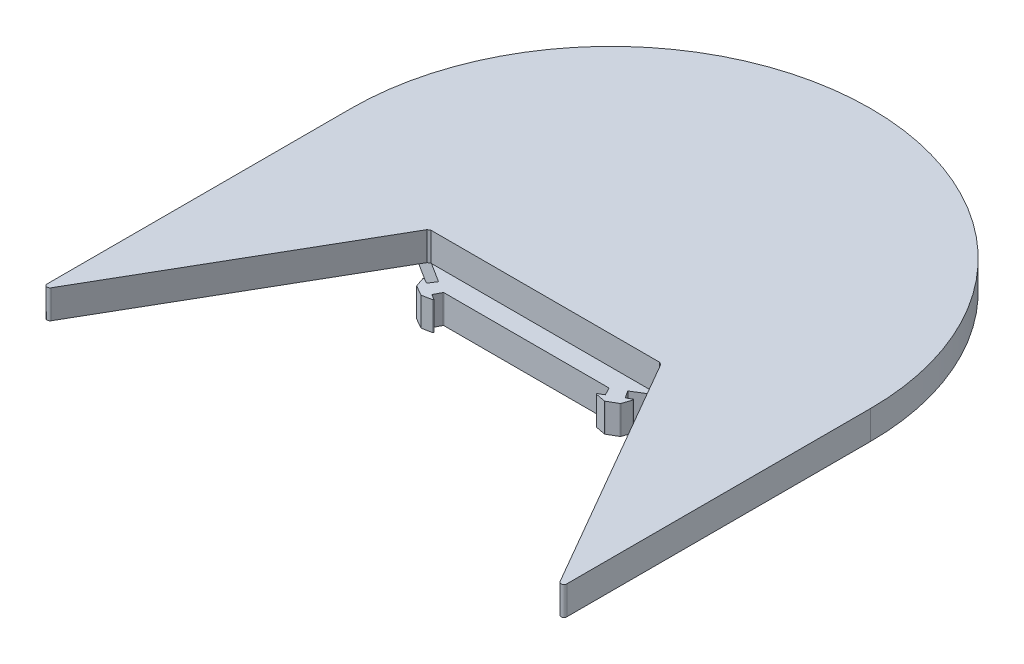
SolidWorks part; units mm, degrees
ref_plane "Plan de face" through (0, 0, 0) normal (0, 0, 1) x (1, 0, 0)
ref_plane "Plan de dessus" through (0, 0, 0) normal (0, 1, 0) x (1, 0, 0)
ref_plane "Plan de droite" through (0, 0, 0) normal (1, 0, 0) x (0, 0, -1)
sketch "Esquisse1" plane through (0, 0, 0) normal (0, 1, 0) x (1, 0, 0)
  line L0 (-20.5353, -16.9035) -> (-20.9683, -16.6535) construction
  line L26 (149.4647, -242.0701) -> (19.4647, -16.9035) construction
  line L32 (-20.5353, -16.9035) -> (-20.5353, -16.4035) construction
  line L34 (-0.5353, -16.4035) -> (-0.5353, 55.2452) construction
  line L35 (-0.5353, -16.9035) -> (-0.5353, -16.4035) construction
  line L38 (-20.5353, -16.9035) -> (19.4647, -16.9035) construction
  line L41 (-20.5353, -16.9035) -> (-20.5353, -16.4035) construction
  line L56 (19.4647, -16.9035) -> (19.4647, -16.4035) construction
  line L57 (19.4647, -16.9035) -> (19.8977, -16.6535) construction
  line L58 (19.4647, -16.9035) -> (24.4647, -25.5637) construction
  line L59 (44.4647, -60.2047) -> (44.8977, -59.9547) construction
  line L60 (19.4647, -16.9035) -> (149.4647, -242.0701) construction
  line L62 (19.4647, -16.4035) -> (-20.5353, -16.4035)
  line L63 (44.8977, -58.0887) -> (44.8977, -4.9547)
  line L64 (19.4647, -16.4035) -> (19.8977, -16.6535)
  line L67 (19.8977, -16.6535) -> (43.9647, -58.3387)
  line L68 (43.9647, -58.3387) -> (44.8977, -59.9547) construction
  line L69 (44.8977, -59.9547) -> (44.8977, -58.0887) construction
  line L70 (-45.9683, -59.9547) -> (-45.9683, -58.0887) construction
  line L71 (-45.0353, -58.3387) -> (-45.9683, -59.9547) construction
  line L72 (-45.5353, -60.2047) -> (-45.9683, -59.9547) construction
  line L73 (-20.5353, -16.9035) -> (-20.9683, -16.6535) construction
  line L74 (-20.5353, -16.9035) -> (-20.5353, -16.4035) construction
  line L75 (-20.9683, -16.6535) -> (-45.0353, -58.3387)
  line L76 (-20.5353, -16.4035) -> (-20.9683, -16.6535)
  line L77 (-45.9683, -58.0887) -> (-45.9683, -4.9547)
  line L78 (-45.5353, -60.2047) -> (-0.5353, -16.9035) construction
  line L79 (-0.5353, -16.9035) -> (44.4647, -60.2047) construction
  line L80 (-20.5353, -16.9035) -> (-0.5353, 17.7376) construction
  line L81 (-0.5353, 17.7376) -> (19.4647, -16.9035) construction
  arc A3 (44.8977, -58.0887) -> (43.9647, -58.3387) centre (44.3977, -58.0887) cw
  arc A4 (-45.9683, -58.0887) -> (-45.0353, -58.3387) centre (-45.4683, -58.0887) ccw
  arc A5 (-45.9683, -4.9547) -> (44.8977, -4.9547) centre (-0.5353, -4.9547) cw
  dimension "D5" = 55
  dimension "D8" = 0.5
  dimension "D1" = 50
  dimension "D2" = 90
  dimension "D3" = 0.5
  dimension "D7" = 90
extrude "Boss.-Extru.1" add sketch "Esquisse1" along normal blind 5
sketch "Esquisse3" plane through (0, 0, 0) normal (0, -1, 0) x (1, 0, 0)
  line L6 (-17.9084, 19.8187) -> (-17.0848, 18.5338)
  line L12 (-16.5857, 22.1096) -> (-18.3585, 21.0861)
  line L35 (-16.5857, 22.1096) -> (-14.6111, 21.7223)
  line L36 (-16.9041, 22.4641) -> (-18.5063, 21.539) construction
  line L37 (-14.377, 22.0186) -> (-16.7656, 22.4871) construction
  line L38 (-15.2329, 21.1195) -> (-14.3155, 21.6492) construction
  line L39 (-15.7132, 21.0861) -> (-14.6111, 21.7223)
  line L40 (-17.4721, 21.5978) -> (-16.2052, 19.4035) construction
  line L42 (-18.3585, 21.0861) -> (-19.0104, 19.1824)
  line L43 (-17.9084, 19.8187) -> (-19.0104, 19.1824)
  line L62 (-15.7132, 21.0861) -> (-15.0122, 19.7303)
  line L70 (-16.2052, 19.4035) -> (-21.2052, 28.0637) construction
  line L74 (-0.5353, 16.4035) -> (-0.5353, 27.1764) construction
  line L78 (-33.5247, 7.0348) -> (33.0032, 7.0348)
  line L79 (-20.5353, 16.4035) -> (19.4647, 16.4035) construction
  line L82 (-0.5353, 16.9035) -> (-0.5353, 47.2624) construction
  line L88 (16.4015, 21.5978) -> (15.1346, 19.4035) construction
  line L89 (17.2879, 21.0861) -> (17.9398, 19.1824)
  line L90 (16.8378, 19.8187) -> (17.9398, 19.1824)
  line L91 (15.5151, 22.1096) -> (13.5405, 21.7223)
  line L92 (14.6425, 21.0861) -> (13.5405, 21.7223)
  line L93 (14.6425, 21.0861) -> (13.9416, 19.7303)
  line L127 (16.8378, 19.8187) -> (16.0141, 18.5338)
  line L138 (15.5151, 22.1096) -> (17.2879, 21.0861)
  line L140 (-15.0122, 19.7303) -> (13.9416, 19.7303)
  line L156 (-17.0848, 18.5338) -> (-33.7921, 7.9573)
  line L157 (16.0141, 18.5338) -> (33.2645, 7.9611)
  arc A29 (33.2645, 7.9611) -> (33.0032, 7.0348) centre (33.0032, 7.5348) cw
  arc A30 (-33.7921, 7.9573) -> (-33.5247, 7.0348) centre (-33.5247, 7.5348) ccw
  dimension "D1" = 0.5
extrude "Boss.-Extru.2" add sketch "Esquisse3" along normal blind 5
fillet "Congé1" radius 0.1 14 edges at (-17.0848, -2.5, 18.5338) (-17.9084, -2.5, 19.8187) (-15.7132, -2.5, 21.0861) (-14.6111, -2.5, 21.7223) (-16.5857, -2.5, 22.1096) (-18.3585, -2.5, 21.0861) (-19.0104, -2.5, 19.1824) (13.9416, -2.5, 19.7303) (-15.0122, -2.5, 19.7303) (13.5405, -2.5, 21.7223) (15.5151, -2.5, 22.1096) (17.2879, -2.5, 21.0861) (17.9398, -2.5, 19.1824) (16.8378, -2.5, 19.8187)
